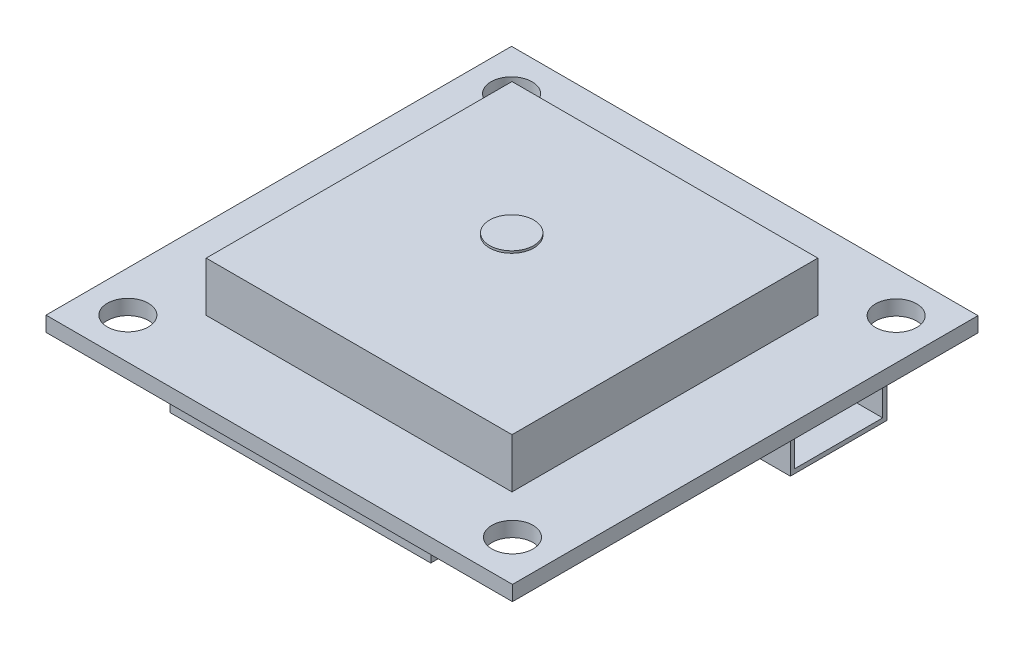
SolidWorks part; units mm, degrees
ref_plane "Front Plane" through (0, 0, 0) normal (0, 0, 1) x (1, 0, 0)
ref_plane "Top Plane" through (0, 0, 0) normal (0, 1, 0) x (1, 0, 0)
ref_plane "Right Plane" through (0, 0, 0) normal (1, 0, 0) x (0, 0, -1)
sketch "Sketch1" plane through (0, 0, 0) normal (0, 1, 0) x (1, 0, 0)
  line L1 (0, 0) -> (38.354, 0)
  line L2 (0, 0) -> (0, 38.2778)
  line L3 (0, 38.2778) -> (38.354, 38.2778)
  line L4 (38.354, 0) -> (38.354, 38.2778)
  dimension "D1" = 38.2778
  dimension "D2" = 38.354
extrude "Board" add sketch "Sketch1" along normal blind 1.2319
sketch "Sketch3" plane through (0, 1.2319, 0) normal (0, 1, 0) x (1, 0, 0)
  line L0 (38.354, 19.1389) -> (31.75, 19.1389) construction
  line L1 (31.75, 31.7119) -> (6.604, 31.7119)
  line L2 (31.75, 31.7119) -> (31.75, 6.5659)
  line L3 (31.75, 6.5659) -> (6.604, 6.5659)
  line L4 (6.604, 31.7119) -> (6.604, 6.5659)
  line L5 (38.354, 0) -> (38.354, 38.2778) construction
  line L6 (19.177, 38.2778) -> (19.177, 31.7119) construction
  line L7 (38.354, 38.2778) -> (0, 38.2778) construction
  dimension "D1" = 25.146
  dimension "D2" = 25.146
extrude "GPS" add sketch "Sketch3" along normal blind 4.0767
sketch "Sketch5" plane through (0, 0, 0) normal (0, -1, 0) x (1, 0, 0)
  line L0 (38.354, 0) -> (38.354, -38.2778) construction
  line L1 (8.382, -1.8161) -> (29.8196, -1.8161)
  line L2 (8.382, -1.8161) -> (8.382, -18.6055)
  line L3 (8.382, -18.6055) -> (29.8196, -18.6055)
  line L4 (29.8196, -1.8161) -> (29.8196, -18.6055)
  line L5 (38.354, -38.2778) -> (0, -38.2778) construction
  dimension "D1" = 21.4376
  dimension "D2" = 16.7894
  dimension "D3" = 29.972
  dimension "D4" = 36.4617
extrude "uBlock chip" add sketch "Sketch5" along normal blind 2.4257
sketch "Sketch6" plane through (0, 0, 0) normal (0, -1, 0) x (-1, 0, 0)
  line L0 (-22.2758, 29.2481) -> (-18.8131, 29.2481) construction
  line L1 (-38.354, 38.2778) -> (0, 38.2778) construction
  line L2 (-18.8976, 32.6263) -> (-18.8976, 25.0521) construction
  line L3 (-38.354, 0) -> (-38.354, 38.2778) construction
  circle A0 centre (-22.2758, 32.6263) radius 3.3782
  dimension "D1" = 6.7564
  dimension "D2" = 9.0297
  dimension "D3" = 19.4564
extrude "Battery" add sketch "Sketch6" along normal blind 2.1082
sketch "Sketch7" plane through (0, 0, 0) normal (0, -1, 0) x (-1, 0, 0)
  line L0 (-38.354, 38.2778) -> (0, 38.2778) construction
  line L1 (-33.528, 23.3553) -> (-37.846, 23.3553)
  line L2 (-33.528, 23.3553) -> (-33.528, 31.3055)
  line L3 (-33.528, 31.3055) -> (-37.846, 31.3055)
  line L4 (-37.846, 23.3553) -> (-37.846, 31.3055)
  line L5 (-38.354, 0) -> (-38.354, 38.2778) construction
  dimension "D1" = 7.9502
  dimension "D2" = 4.318
  dimension "D3" = 14.9225
  dimension "D4" = 4.826
extrude "Connector" add sketch "Sketch7" along normal blind 2.9972
sketch "Sketch8" plane through (37.846, 0, 0) normal (1, 0, 0) x (0, 0, -1)
  line L0 (31.3055, 0) -> (23.3553, 0) construction
  line L1 (23.7109, -0.3556) -> (30.9499, -0.3556)
  line L2 (23.7109, -0.3556) -> (23.7109, -2.6416)
  line L3 (23.7109, -2.6416) -> (30.9499, -2.6416)
  line L4 (30.9499, -0.3556) -> (30.9499, -2.6416)
  line L5 (31.3055, -2.9972) -> (23.3553, -2.9972) construction
  line L6 (23.3553, -2.9972) -> (23.3553, 0) construction
  line L7 (31.3055, -2.9972) -> (31.3055, 0) construction
  dimension "D1" = 0.3556
  dimension "D2" = 0.3556
  dimension "D3" = 0.3556
  dimension "D4" = 0.3556
extrude "Cut-Extrude1" cut sketch "Sketch8" against normal blind 3.7592
sketch "Sketch9" plane through (0, 1.2319, 0) normal (0, 1, 0) x (1, 0, 0)
  line L0 (36.6776, 3.3655) -> (38.354, 3.3655) construction
  line L1 (34.9885, 1.6764) -> (34.9885, 0) construction
  line L2 (0, 0) -> (38.354, 0) construction
  line L3 (1.6764, 3.3655) -> (0, 3.3655) construction
  line L4 (38.354, 0) -> (38.354, 38.2778) construction
  line L5 (0, 38.2778) -> (0, 0) construction
  line L6 (34.9885, 36.6014) -> (34.9885, 38.2778) construction
  line L7 (38.354, 38.2778) -> (0, 38.2778) construction
  circle A0 centre (34.9885, 3.3655) radius 1.6891
  circle A1 centre (3.3655, 3.3655) radius 1.6891
  circle A2 centre (3.3655, 34.9123) radius 1.6891
  circle A3 centre (34.9885, 34.9123) radius 1.6891
  dimension "D1" = 3.3782
  dimension "D2" = 1.6764
extrude "Cut-Extrude2" cut sketch "Sketch9" against normal up to next
sketch "Sketch10" plane through (0, 5.3086, 0) normal (0, 1, 0) x (1, 0, 0)
  line L0 (17.5387, 22.5679) -> (22.9587, 22.5679) construction
  line L1 (15.7226, 20.7518) -> (15.7226, 15.1271) construction
  line L2 (6.604, 6.5659) -> (31.75, 6.5659) construction
  line L3 (31.75, 6.5659) -> (31.75, 31.7119) construction
  circle A0 centre (17.5387, 20.7518) radius 1.8161
  dimension "D1" = 3.6322
  dimension "D2" = 16.002
  dimension "D3" = 16.0274
extrude "Boss-Extrude6" add sketch "Sketch10" along normal blind 0.1778
